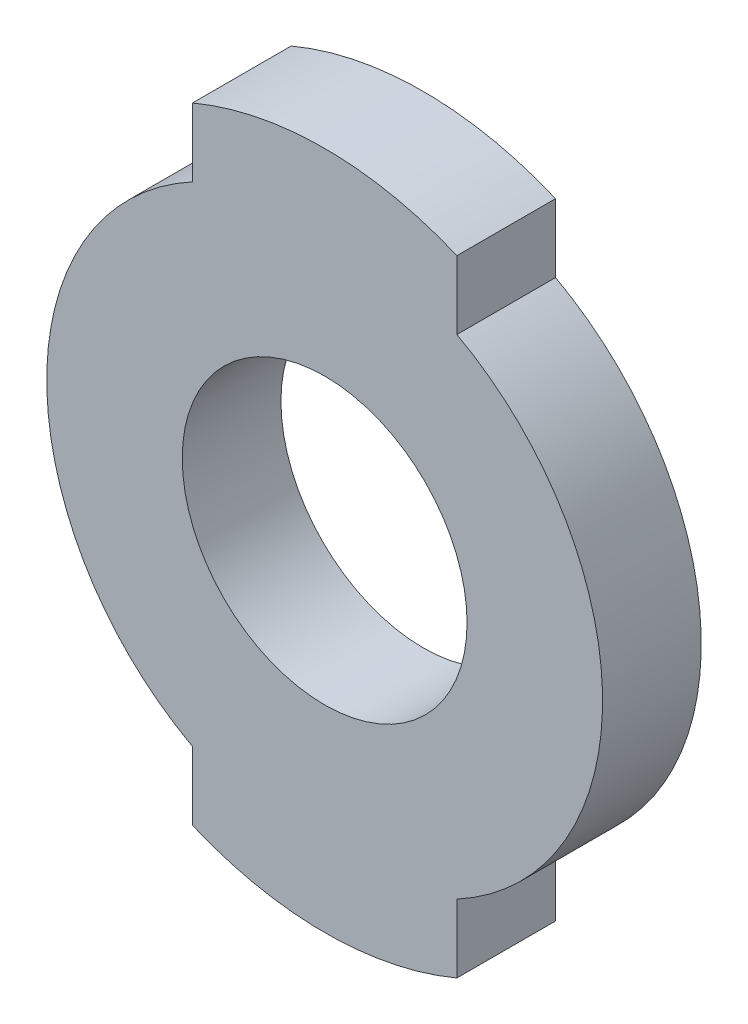
SolidWorks part; units mm, degrees
material "1.5714 (16NiCr4)"
ref_plane "Ön Düzlem" through (0, 0, 0) normal (0, 0, 1) x (1, 0, 0)
ref_plane "Üst Düzlem" through (0, 0, 0) normal (0, 1, 0) x (1, 0, 0)
ref_plane "Sağ Düzlem" through (0, 0, 0) normal (1, 0, 0) x (0, 0, -1)
sketch "Çizim1" plane through (0, 0, 0) normal (0, 0, 1) x (1, 0, 0)
  circle A0 centre (0, 0) radius 20.65
  dimension "D1" = 41.3
extrude "Yükseklik-Ekstrüzyon1" add sketch "Çizim1" along normal blind 6
sketch "Çizim3" plane through (0, 0, 6) normal (0, 0, 1) x (1, 0, 0)
  line L0 (0, 0) -> (8.04, 0) construction
  line L1 (8.04, 14.865) -> (8.04, 19.0205)
  line L2 (8.04, -14.865) -> (8.04, -19.0205)
  line L4 (-8.04, 14.865) -> (-8.04, 19.0205)
  line L5 (-8.04, -14.865) -> (-8.04, -19.0205)
  arc A0 (-8.04, 14.865) -> (-8.04, -14.865) centre (0, 0) ccw
  circle A1 centre (0, 0) radius 20.65 construction
  arc A2 (-8.04, 19.0205) -> (-8.04, -19.0205) centre (0, 0) ccw
  arc A3 (8.04, -19.0205) -> (8.04, 19.0205) centre (0, 0) ccw
  arc A4 (8.04, -14.865) -> (8.04, 14.865) centre (0, 0) ccw
extrude "Kes-Ekstrüzyon1" cut sketch "Çizim3" against normal blind 6
sketch "Çizim4" plane through (0, 0, 6) normal (0, 0, 1) x (1, 0, 0)
  circle A0 centre (0, 0) radius 8.66
extrude "Kes-Ekstrüzyon2" cut sketch "Çizim4" against normal blind 6
